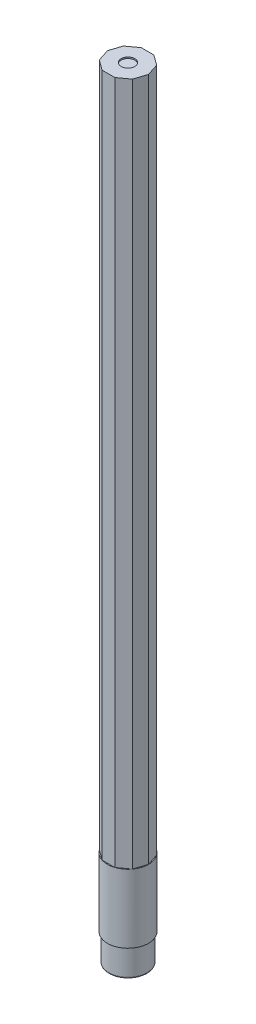
SolidWorks part; units mm, degrees
ref_plane "Front Plane" through (0, 0, 0) normal (0, 0, 1) x (1, 0, 0)
ref_plane "Top Plane" through (0, 0, 0) normal (0, 1, 0) x (1, 0, 0)
ref_plane "Right Plane" through (0, 0, 0) normal (1, 0, 0) x (0, 0, -1)
sketch "Sketch2" plane through (0, 0, 0) normal (0, 1, 0) x (1, 0, 0)
  circle A0 centre (0, 0) radius 3.81
  dimension "D1" = 7.62
extrude "Boss-Extrude1" add sketch "Sketch2" along normal blind 12.7
sketch "Sketch3" plane through (0, 12.7, 0) normal (0, 1, 0) x (1, 0, 0)
  line L0 (0, 5.4134) -> (0, 0) construction
  line L1 (3.81, 0) -> (3.0824, 2.2395)
  line L2 (3.0824, 2.2395) -> (1.1774, 3.6235)
  line L3 (1.1774, 3.6235) -> (-1.1774, 3.6235)
  line L4 (-1.1774, 3.6235) -> (-3.0824, 2.2395)
  line L5 (-3.0824, 2.2395) -> (-3.81, 0)
  line L6 (-3.81, 0) -> (-3.0824, -2.2395)
  line L7 (-3.0824, -2.2395) -> (-1.1774, -3.6235)
  line L8 (-1.1774, -3.6235) -> (1.1774, -3.6235)
  line L9 (1.1774, -3.6235) -> (3.0824, -2.2395)
  line L10 (3.0824, -2.2395) -> (3.81, 0)
  circle A0 centre (0, 0) radius 3.6235 construction
  circle A1 centre (0, 0) radius 3.81 construction
  dimension "D1" = 90
extrude "Boss-Extrude2" add sketch "Sketch3" along normal blind 127
sketch "Sketch4" plane through (0, 0, 0) normal (0, -1, 0) x (1, 0, 0)
  circle A0 centre (0, 0) radius 3.556
  dimension "D1" = 7.112
extrude "Boss-Extrude3" add sketch "Sketch4" along normal blind 5.08
fillet "Fillet3" radius 0.254 1 edges at (0, -5.08, -3.556)
sketch "Sketch5" plane through (0, 139.7, 0) normal (0, 1, 0) x (1, 0, 0)
  circle A0 centre (0, 0) radius 1.27
  dimension "D1" = 2.54
extrude "Cut-Extrude1" cut sketch "Sketch5" against normal blind 0.254
sketch "Sketch6" plane through (2.1299, 0, -2.9315) normal (0.5878, 0, -0.809) x (-0.809, 0, -0.5878)
  text T0 "HENNEY"
